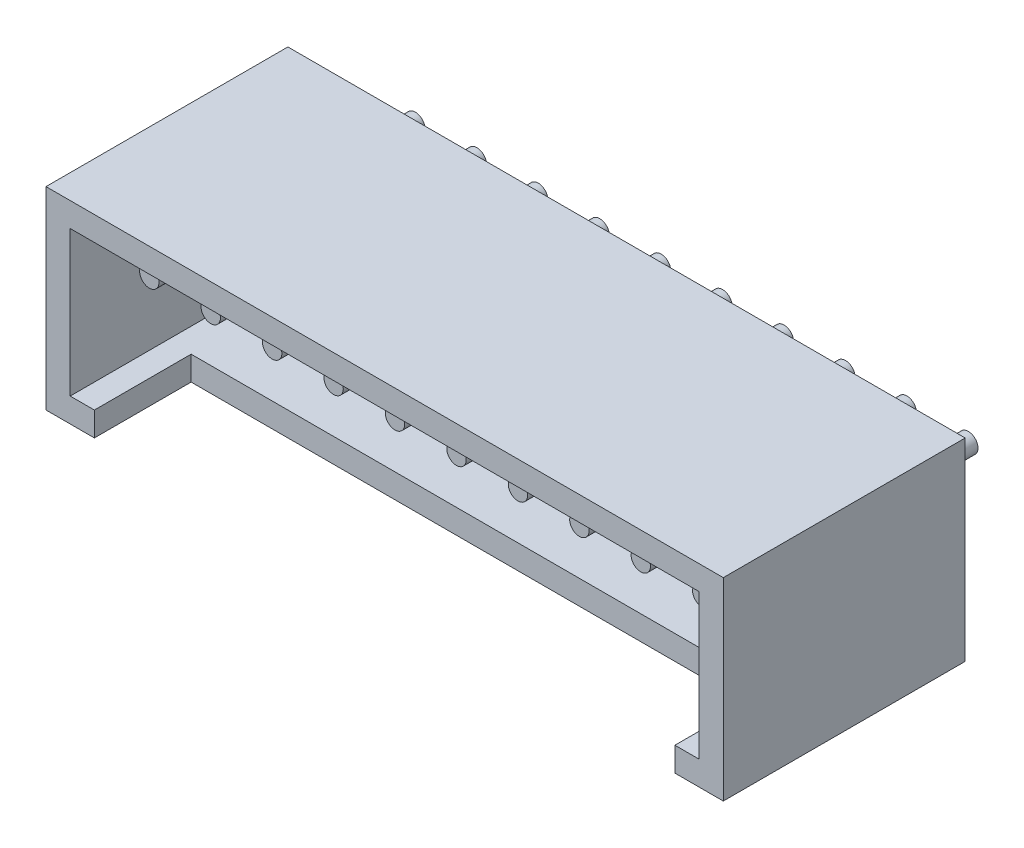
SolidWorks part; units mm, degrees
ref_plane "前视基准面" through (0, 0, 0) normal (0, 0, 1) x (1, 0, 0)
ref_plane "上视基准面" through (0, 0, 0) normal (0, 1, 0) x (1, 0, 0)
ref_plane "右视基准面" through (0, 0, 0) normal (1, 0, 0) x (0, 0, -1)
sketch "草图1" plane through (0, 0, 0) normal (0, 0, 1) x (1, 0, 0)
  line L1 (0, 0) -> (14, 0)
  line L2 (0, 0) -> (0, 4)
  line L3 (0, 4) -> (14, 4)
  line L4 (14, 0) -> (14, 4)
  dimension "D1" = 4
  dimension "D2" = 14
extrude "凸台-拉伸1" add sketch "草图1" along normal blind 5
sketch "草图2" plane through (0, 0, 5) normal (0, 0, 1) x (1, 0, 0)
  line L8 (0.5, 3.5) -> (0.5, 0.5)
  line L9 (0.5, 0.5) -> (13.5, 0.5)
  line L10 (13.5, 0.5) -> (13.5, 3.5)
  line L11 (13.5, 3.5) -> (0.5, 3.5)
  line L12 (0.5, 3.5) -> (0.5, 0.5)
  line L13 (0.5, 0.5) -> (13.5, 0.5)
  line L14 (13.5, 0.5) -> (13.5, 3.5)
  line L15 (13.5, 3.5) -> (0.5, 3.5)
  dimension "D1" = 0.5
extrude "切除-拉伸1" cut sketch "草图2" against normal blind 3.6
sketch "草图3" plane through (0, 0, 0) normal (0, -1, 0) x (1, 0, 0)
  line L0 (7, 0.5573) -> (7, 5.5573) construction
  line L3 (0, 5) -> (14, 5) construction
  line L4 (1, 6.7375) -> (13, 6.7375)
  line L5 (1, 6.7375) -> (1, 3)
  line L6 (1, 3) -> (13, 3)
  line L7 (13, 6.7375) -> (13, 3)
  point P5 (7, 3)
  point P10 (7, 6.7375)
  dimension "D1" = 12
  dimension "D2" = 2
extrude "切除-拉伸2" cut sketch "草图3" against normal up to next
sketch "草图4" plane through (0, 0, 1.4) normal (0, 0, 1) x (1, 0, 0)
  line L0 (-0.6584, 2.6) -> (16.6991, 2.6) construction
  line L1 (14, 4) -> (0, 4) construction
  line L2 (7, 4) -> (7, -0.1439) construction
  circle A0 centre (1.285, 2.6) radius 0.2
  dimension "D2" = 0.4
  dimension "D3" = 11.43
  dimension "D1" = 1.4
extrude "凸台-拉伸2" add sketch "草图4" along normal mid plane 5.5
pattern_linear "阵列(线性)1" count 10 spacing 1.27 along (1, 0, 0) of "凸台-拉伸2"
